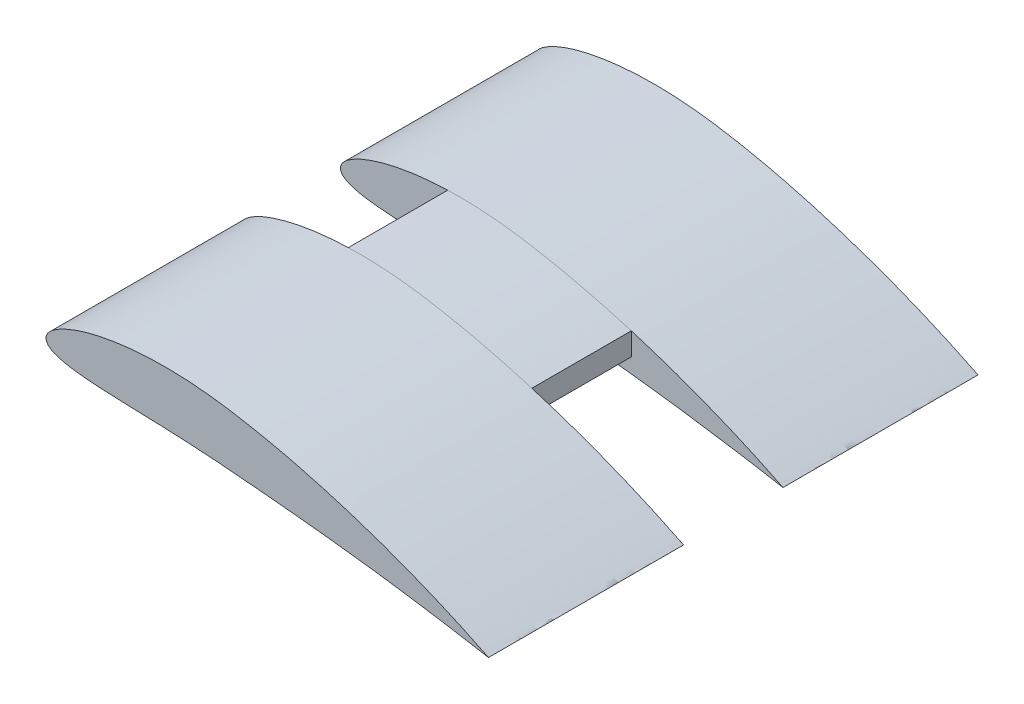
SolidWorks part; units mm, degrees
ref_plane "Front Plane" through (0, 0, 0) normal (0, 0, 1) x (1, 0, 0)
ref_plane "Top Plane" through (0, 0, 0) normal (0, 1, 0) x (1, 0, 0)
ref_plane "Right Plane" through (0, 0, 0) normal (1, 0, 0) x (0, 0, -1)
sketch "Sketch1" plane through (0, 0, 0) normal (0, 0, 1) x (1, 0, 0)
  line L0 (-3993.7435, 2773.6082) -> (-3841.3435, 2773.6082)
  line L1 (-3993.7435, 2817.2584) -> (-3993.7435, 2773.6082)
  line L2 (-3841.3435, 2792.3631) -> (-3841.3435, 2773.6082)
  spline S0 degree 3 poles (-3841.3435, 2792.3631) (-3841.7119, 2792.4756) (-3843.8981, 2793.1398) (-3847.9388, 2794.3128) (-3853.4729, 2795.891) (-3859.0791, 2797.4234) (-3864.7079, 2798.9922) (-3870.3976, 2800.4561) (-3876.1034, 2801.9237) (-3881.8598, 2803.2691) (-3887.6092, 2804.6713) (-3893.3883, 2805.9815) (-3899.1862, 2807.1795) (-3904.9732, 2808.4652) (-3910.7888, 2809.5332) (-3916.567, 2810.7021) (-3922.3529, 2811.6805) (-3928.1352, 2812.6557) (-3933.932, 2813.6081) (-3939.7469, 2814.4327) (-3945.5514, 2815.1325) (-3951.3253, 2815.784) (-3957.0542, 2816.2853) (-3962.7292, 2816.7371) (-3968.3327, 2817.0388) (-3973.8845, 2817.2857) (-3979.3506, 2817.3921) (-3984.7406, 2817.4187) (-3989.5232, 2817.3661) (-3992.5167, 2817.2954) (-3993.7435, 2817.2584) knots 5.335664 5.335664 5.335664 5.335664 5.381152 5.605544 5.832583 6.060843 6.291984 6.522722 6.754716 6.98781 7.220903 7.453687 7.687649 7.920159 8.15378 8.385948 8.6164 8.846783 9.078562 9.310218 9.540375 9.769095 9.996455 10.219563 10.441458 10.659209 10.875904 11.087124 11.295818 11.440781 11.440781 11.440781 11.440781
extrude "Boss-Extrude1" add sketch "Sketch1" along normal blind 82.55
sketch "Sketch2" plane through (0, 0, 82.55) normal (0, 0, 1) x (1, 0, 0)
  spline S0 degree 3 poles (-3715.6401, 2742.69) (-3715.39, 2742.6389) (-3715.6038, 2742.764) (-3715.8334, 2742.8012) (-3716.2462, 2743.104) (-3716.8538, 2743.32) (-3717.586, 2743.7365) (-3718.5226, 2744.1695) (-3719.5997, 2744.7298) (-3720.8707, 2745.3086) (-3722.2735, 2746.027) (-3723.8705, 2746.7651) (-3725.6095, 2747.6216) (-3727.5323, 2748.5186) (-3729.5805, 2749.5336) (-3731.8241, 2750.5273) (-3734.1815, 2751.6644) (-3736.7258, 2752.8067) (-3739.3945, 2754.0982) (-3742.2581, 2755.3592) (-3745.2524, 2756.6904) (-3748.3722, 2758.1067) (-3751.6743, 2759.486) (-3755.0788, 2761.0033) (-3758.6327, 2762.5214) (-3762.3274, 2764.0493) (-3766.1596, 2765.6348) (-3770.1075, 2767.2923) (-3774.2124, 2768.8878) (-3778.4066, 2770.5809) (-3782.7395, 2772.2568) (-3787.1893, 2773.9616) (-3791.7404, 2775.6692) (-3796.3962, 2777.4054) (-3801.1503, 2779.1449) (-3806.0276, 2780.8533) (-3810.979, 2782.5892) (-3816.033, 2784.2788) (-3821.1651, 2785.9927) (-3826.363, 2787.7249) (-3831.6732, 2789.37) (-3837.038, 2791.0266) (-3842.4511, 2792.7198) (-3847.9388, 2794.3128) (-3853.4729, 2795.891) (-3859.0791, 2797.4234) (-3864.7079, 2798.9922) (-3870.3976, 2800.4561) (-3876.1034, 2801.9237) (-3881.8598, 2803.2691) (-3887.6092, 2804.6713) (-3893.3883, 2805.9815) (-3899.1862, 2807.1795) (-3904.9732, 2808.4652) (-3910.7888, 2809.5332) (-3916.567, 2810.7021) (-3922.3529, 2811.6805) (-3928.1352, 2812.6557) (-3933.932, 2813.6081) (-3939.7469, 2814.4327) (-3945.5514, 2815.1325) (-3951.3253, 2815.784) (-3957.0542, 2816.2853) (-3962.7292, 2816.7371) (-3968.3327, 2817.0388) (-3973.8845, 2817.2857) (-3979.3506, 2817.3921) (-3984.7406, 2817.4187) (-3990.0418, 2817.3604) (-3995.2544, 2817.2259) (-4000.3655, 2816.9917) (-4005.3638, 2816.6775) (-4010.245, 2816.264) (-4015.0147, 2815.8121) (-4019.6569, 2815.2702) (-4024.1679, 2814.6229) (-4028.5413, 2813.934) (-4032.7711, 2813.1832) (-4036.8506, 2812.3948) (-4040.7723, 2811.5029) (-4044.5658, 2810.6674) (-4048.1766, 2809.676) (-4051.6267, 2808.6765) (-4054.9217, 2807.6869) (-4058.0182, 2806.5948) (-4060.9733, 2805.5513) (-4063.7239, 2804.4428) (-4066.3077, 2803.3284) (-4068.7102, 2802.2326) (-4070.9145, 2801.0618) (-4072.9455, 2799.9233) (-4074.7733, 2798.7418) (-4076.4416, 2797.6337) (-4077.9044, 2796.4819) (-4079.1816, 2795.3628) (-4080.2825, 2794.2486) (-4081.1581, 2793.126) (-4081.8802, 2792.0267) (-4082.3345, 2790.9142) (-4082.6751, 2789.8479) (-4082.8233, 2788.7849) (-4082.6939, 2787.7456) (-4082.47, 2786.7232) (-4081.9635, 2785.773) (-4081.3104, 2784.8697) (-4080.533, 2783.9569) (-4079.4788, 2783.1958) (-4078.3186, 2782.4063) (-4076.9716, 2781.6801) (-4075.4383, 2781.0213) (-4073.7439, 2780.3626) (-4071.8753, 2779.7636) (-4069.8366, 2779.2263) (-4067.6544, 2778.69) (-4065.2979, 2778.2242) (-4062.8051, 2777.7769) (-4060.1539, 2777.3098) (-4057.3435, 2777.0123) (-4054.3976, 2776.6116) (-4051.2999, 2776.344) (-4048.0738, 2775.9889) (-4044.6998, 2775.7458) (-4041.2012, 2775.4955) (-4037.5624, 2775.2778) (-4033.8098, 2775.0694) (-4029.9298, 2774.9143) (-4025.9515, 2774.686) (-4021.8434, 2774.6035) (-4017.6401, 2774.3863) (-4013.3223, 2774.2387) (-4008.9157, 2774.1132) (-4004.4102, 2773.9694) (-3999.819, 2773.8178) (-3995.1293, 2773.638) (-3990.3514, 2773.5228) (-3985.4903, 2773.3198) (-3980.5564, 2773.1252) (-3975.5494, 2772.9324) (-3970.485, 2772.6688) (-3965.3596, 2772.4153) (-3960.1736, 2772.1592) (-3954.9178, 2771.8516) (-3949.6185, 2771.479) (-3944.2685, 2771.1527) (-3938.8684, 2770.6851) (-3933.3687, 2770.2429) (-3927.7971, 2769.7725) (-3922.1621, 2769.3252) (-3916.5105, 2768.7847) (-3910.8261, 2768.3414) (-3905.1491, 2767.8133) (-3899.4586, 2767.3032) (-3893.7554, 2766.8005) (-3888.0581, 2766.2376) (-3882.3724, 2765.6876) (-3876.6973, 2765.1582) (-3871.0434, 2764.5409) (-3865.3906, 2764.0411) (-3859.7901, 2763.3953) (-3854.2225, 2762.7957) (-3848.6931, 2762.1868) (-3843.199, 2761.5967) (-3837.759, 2760.9665) (-3832.3862, 2760.2967) (-3827.0731, 2759.6476) (-3821.8219, 2758.9997) (-3816.6549, 2758.3743) (-3811.5661, 2757.7172) (-3806.5723, 2757.0021) (-3801.6392, 2756.3898) (-3796.8036, 2755.7) (-3792.06, 2755.0626) (-3787.4242, 2754.366) (-3782.9078, 2753.7043) (-3778.5022, 2753.0514) (-3774.2197, 2752.4087) (-3770.0434, 2751.8034) (-3766.0029, 2751.1264) (-3762.0685, 2750.5665) (-3758.2857, 2749.918) (-3754.633, 2749.3909) (-3751.1414, 2748.7922) (-3747.7912, 2748.2433) (-3744.5815, 2747.6786) (-3741.5158, 2747.225) (-3738.6275, 2746.6845) (-3735.8797, 2746.2706) (-3733.3087, 2745.7766) (-3730.8832, 2745.3806) (-3728.6314, 2744.9962) (-3726.5556, 2744.6095) (-3724.6483, 2744.3331) (-3722.9301, 2743.9796) (-3721.3809, 2743.7312) (-3720.0065, 2743.4898) (-3718.8192, 2743.2491) (-3717.803, 2743.1197) (-3716.9778, 2742.9239) (-3716.3553, 2742.793) (-3715.8377, 2742.7671) (-3715.6401, 2742.69) (-3715.39, 2742.6389) (-3715.6038, 2742.764) knots -0.001121 -0.000489 -0.000146 0 0.000109 0.000509 0.001141 0.001955 0.003092 0.004429 0.006027 0.00787 0.009929 0.012233 0.014798 0.017563 0.02059 0.023801 0.027226 0.030898 0.034785 0.038903 0.04322 0.047692 0.052396 0.057314 0.062372 0.067617 0.073062 0.078707 0.084481 0.090407 0.096522 0.102778 0.109176 0.115668 0.12235 0.129115 0.136023 0.143016 0.150104 0.157334 0.164595 0.171999 0.17945 0.186933 0.194504 0.202116 0.209825 0.217519 0.225256 0.233029 0.240802 0.248565 0.256367 0.264121 0.271911 0.279654 0.287339 0.295022 0.302751 0.310476 0.318152 0.325779 0.333361 0.340801 0.348201 0.355462 0.362689 0.369732 0.376692 0.383569 0.390269 0.396843 0.403293 0.409563 0.415713 0.421699 0.427511 0.433151 0.43862 0.443874 0.448991 0.453917 0.458618 0.463141 0.467464 0.471548 0.475483 0.479141 0.482632 0.48588 0.488969 0.491799 0.49445 0.496854 0.499125 0.501136 0.503011 0.504728 0.506296 0.507725 0.509134 0.510478 0.511831 0.513232 0.514676 0.516226 0.517925 0.519772 0.521756 0.523938 0.526342 0.528914 0.531662 0.534645 0.537763 0.541121 0.544621 0.548362 0.552248 0.55633 0.560606 0.565031 0.569652 0.574421 0.579388 0.584455 0.589716 0.595081 0.600636 0.606292 0.612098 0.618 0.624047 0.630191 0.636485 0.642871 0.649354 0.655933 0.662606 0.669328 0.676146 0.683058 0.690064 0.69707 0.704168 0.711412 0.718801 0.726191 0.733676 0.741163 0.748647 0.756132 0.763666 0.771198 0.778681 0.786165 0.793647 0.801082 0.808515 0.815851 0.823138 0.830426 0.837615 0.844708 0.851751 0.858698 0.865547 0.872251 0.878907 0.885417 0.89183 0.898146 0.904268 0.910293 0.916125 0.92181 0.92735 0.932745 0.937945 0.943001 0.947861 0.95248 0.956953 0.961233 0.965316 0.969158 0.972805 0.976259 0.979468 0.982484 0.985257 0.987784 0.990072 0.992163 0.993963 0.995569 0.99693 0.998004 0.998879 0.999511 0.999854 1 1.000109 1.000509 1.001141 only from (-3715.4367, 2742.6588) to (-3715.4367, 2742.6588)
  point P0 (0, 0.001)
  point P1 (0.001, 0.001)
  point P2 (0.001, 0)
extrude "Boss-Extrude2" add sketch "Sketch2" along normal blind 161.8945
ref_plane "Plane4" through (0, 0, 41.275) normal (0, 0, -1) x (-1, 0, 0)
mirror "Mirror1" about plane through (0, 0, 41.275) normal (0, 0, -1) of "Boss-Extrude2"
